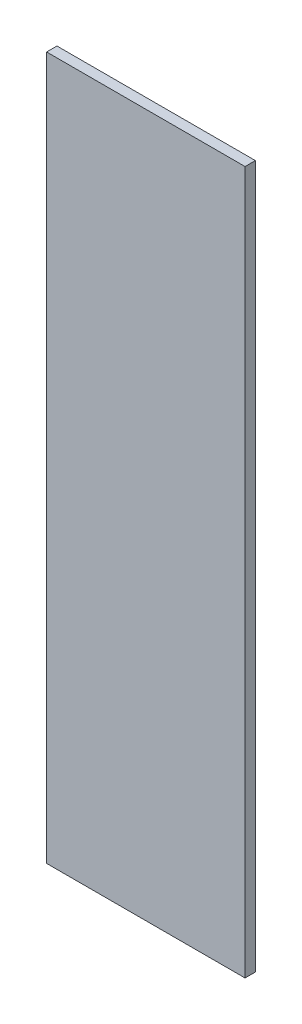
SolidWorks part; units mm, degrees
material "PC High Viscosity"
ref_plane "Front Plane" through (0, 0, 0) normal (0, 0, 1) x (1, 0, 0)
ref_plane "Top Plane" through (0, 0, 0) normal (0, 1, 0) x (1, 0, 0)
ref_plane "Right Plane" through (0, 0, 0) normal (1, 0, 0) x (0, 0, -1)
sketch "Sketch1" plane through (0, 0, 0) normal (0, 0, 1) x (1, 0, 0)
  line L1 (-48, -170) -> (48, -170)
  line L2 (-48, -170) -> (-48, 170)
  line L3 (-48, 170) -> (48, 170)
  line L4 (48, -170) -> (48, 170)
  line L5 (-48, -170) -> (48, 170) construction
  line L6 (-48, 170) -> (48, -170) construction
  point P0 (0, 0)
  dimension "D1" = 96
  dimension "D2" = 340
extrude "Boss-Extrude1" add sketch "Sketch1" along normal mid plane 5
